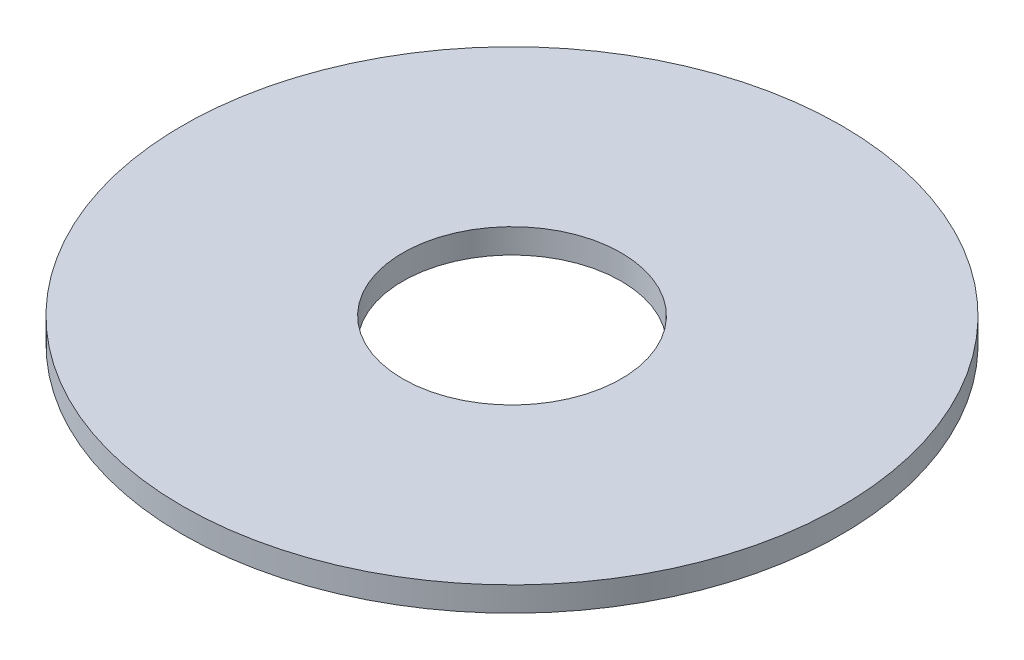
SolidWorks part; units mm, degrees
material "Rubber"
ref_plane "Front Plane" through (0, 0, 0) normal (0, 0, 1) x (1, 0, 0)
ref_plane "Top Plane" through (0, 0, 0) normal (0, 1, 0) x (1, 0, 0)
ref_plane "Right Plane" through (0, 0, 0) normal (1, 0, 0) x (0, 0, -1)
sketch "Sketch1" plane through (0, 0, 0) normal (0, 1, 0) x (1, 0, 0)
  circle A0 centre (0, 0) radius 134.275
  circle A1 centre (0, 0) radius 44.5
  dimension "D1" = 268.55
  dimension "D2" = 89
extrude "Boss-Extrude1" add sketch "Sketch1" along normal blind 10
